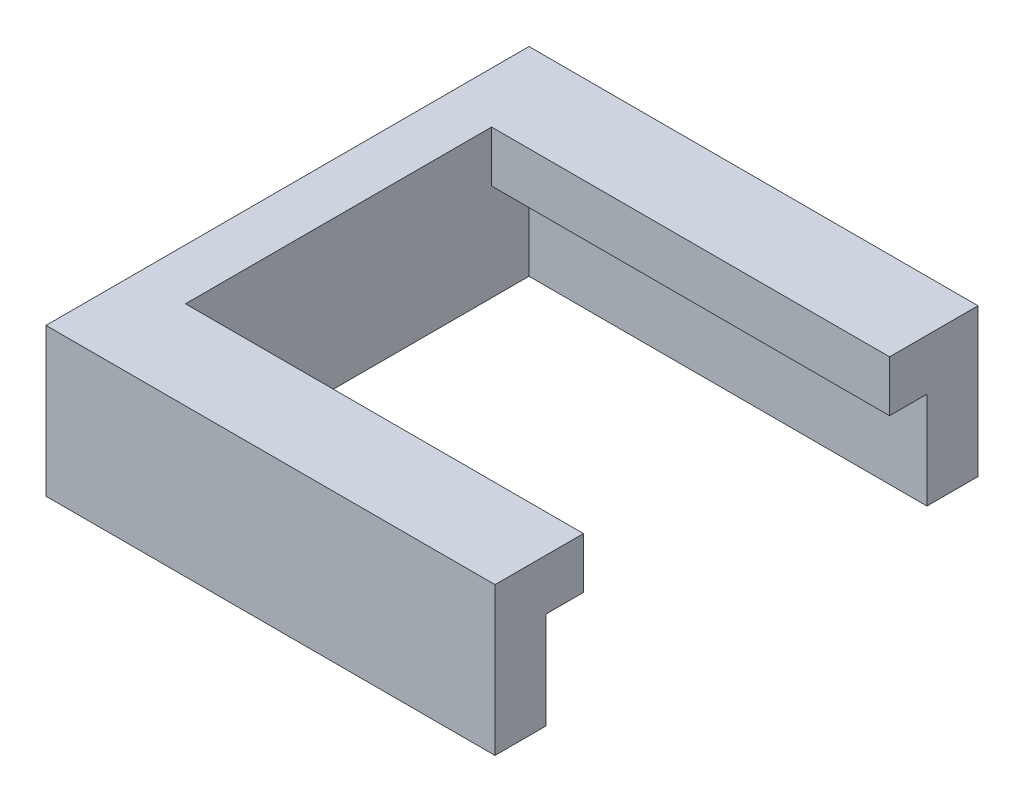
SolidWorks part; units mm, degrees
ref_plane "Alzado" through (0, 0, 0) normal (0, 0, 1) x (1, 0, 0)
ref_plane "Planta" through (0, 0, 0) normal (0, 1, 0) x (1, 0, 0)
ref_plane "Vista lateral" through (0, 0, 0) normal (1, 0, 0) x (0, 0, -1)
sketch "Croquis1" plane through (0, 0, 0) normal (0, 1, 0) x (1, 0, 0)
  line L1 (-10.7383, 18.7027) -> (15.6617, 18.7027)
  line L2 (-10.7383, 18.7027) -> (-10.7383, -9.6973)
  line L3 (-10.7383, -9.6973) -> (15.6617, -9.6973)
  line L4 (15.6617, 18.7027) -> (15.6617, -9.6973)
  dimension "D1" = 28.4
  dimension "D2" = 26.4
extrude "Saliente-Extruir1" add sketch "Croquis1" along normal blind 8.7
sketch "Croquis2" plane through (15.6617, 0, 0) normal (1, 0, 0) x (0, 0, -1)
  line L1 (18.7027, 0) -> (-9.6973, 0) construction
  line L4 (-6.6973, 0) -> (15.7027, 0)
  line L5 (-6.6973, 0) -> (-6.6973, 5.7)
  line L6 (-6.6973, 5.7) -> (15.7027, 5.7)
  line L7 (15.7027, 0) -> (15.7027, 5.7)
extrude "Cortar-Extruir1" cut sketch "Croquis2" against normal blind 23.4
sketch "Croquis3" plane through (15.6617, 0, 0) normal (1, 0, 0) x (0, 0, -1)
  line L1 (15.7027, 5.7) -> (-6.6973, 5.7) construction
  line L3 (-9.6973, 8.7) -> (18.7027, 8.7) construction
  line L4 (-4.4973, 5.7) -> (13.5027, 5.7)
  line L5 (-4.4973, 5.7) -> (-4.4973, 8.7)
  line L6 (-4.4973, 8.7) -> (13.5027, 8.7)
  line L7 (13.5027, 5.7) -> (13.5027, 8.7)
extrude "Cortar-Extruir2" cut sketch "Croquis3" against normal blind 23.4
